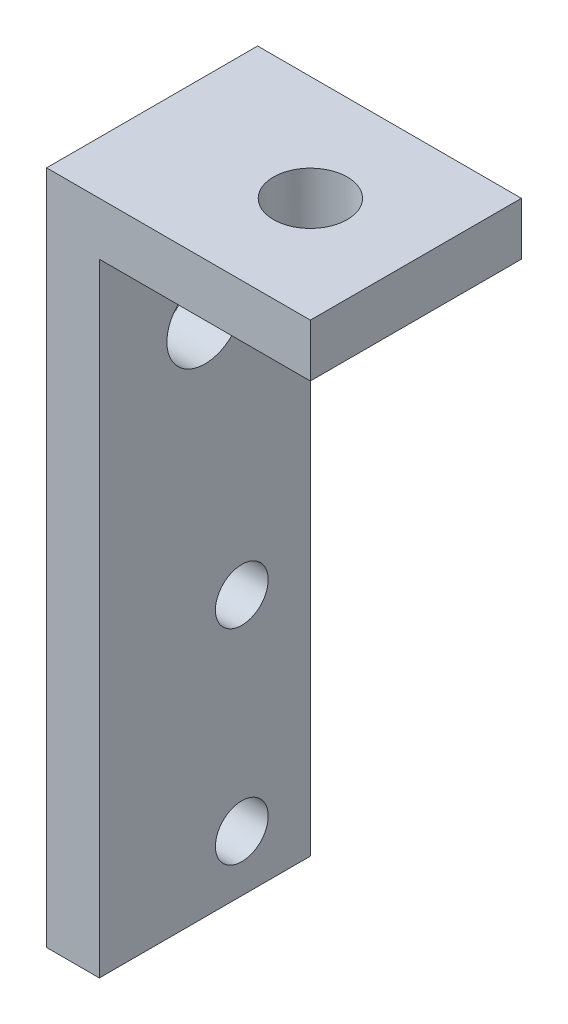
SolidWorks part; units mm, degrees
ref_plane "Front Plane" through (0, 0, 0) normal (0, 0, 1) x (1, 0, 0)
ref_plane "Top Plane" through (0, 0, 0) normal (0, 1, 0) x (1, 0, 0)
ref_plane "Right Plane" through (0, 0, 0) normal (1, 0, 0) x (0, 0, -1)
sketch "Sketch1" plane through (0, 0, 0) normal (0, 0, 1) x (1, 0, 0)
  line L0 (0, 39.5625) -> (0, -32.0625) construction
  line L1 (-37.375, 0) -> (58.375, 0) construction
  line L2 (0, 0) -> (0, 36.5)
  line L3 (0, 36.5) -> (12.5, 36.5)
  line L4 (12.5, 36.5) -> (12.5, 34)
  line L5 (12.5, 34) -> (2.5, 34)
  line L6 (2.5, 34) -> (2.5, 0)
  line L7 (2.5, 0) -> (0, 0)
  dimension "D1" = 2.5
  dimension "D2" = 2.5
  dimension "D3" = 10
  dimension "D4" = 34
extrude "Boss-Extrude1" add sketch "Sketch1" along normal blind 10
sketch "Sketch2" plane through (0, 34, 0) normal (0, -1, 0) x (1, 0, 0)
  circle A0 centre (7.5, 5) radius 1.75
  dimension "D1" = 3.5
  dimension "D3" = 7.5
  dimension "D2" = 5
extrude "Cut-Extrude1" cut sketch "Sketch2" against normal blind 10
sketch "Sketch3" plane through (2.5, 0, 0) normal (1, 0, 0) x (0, 0, -1)
  line L0 (-5, 39.5141) -> (-5, -3.4018) construction
  line L1 (-21.2213, 12) -> (22.3467, 12) construction
  line L2 (0, 0) -> (0, 34) construction
  line L4 (-10, 34) -> (0, 34) construction
  circle A0 centre (-3.25, 7.15) radius 1.25
  circle A1 centre (-3.25, 16.85) radius 1.25
  circle A3 centre (-5, 29) radius 1.8
  dimension "D3" = 2.5
  dimension "D5" = 3.25
  dimension "D6" = 3.6
  dimension "D7" = 5
  dimension "D1" = 5
  dimension "D2" = 12
  dimension "D4" = 4.85
extrude "Cut-Extrude2" cut sketch "Sketch3" against normal through all
sketch "Sketch4" plane through (2.5, 0, 0) normal (1, 0, 0) x (0, 0, -1)
  line L1 (0, 0) -> (-13.0225, 0)
  line L2 (0, 0) -> (0, 4.5)
  line L3 (0, 4.5) -> (-13.0225, 4.5)
  line L4 (-13.0225, 0) -> (-13.0225, 4.5)
  dimension "D1" = 4.5
extrude "Cut-Extrude3" cut sketch "Sketch4" against normal through all
